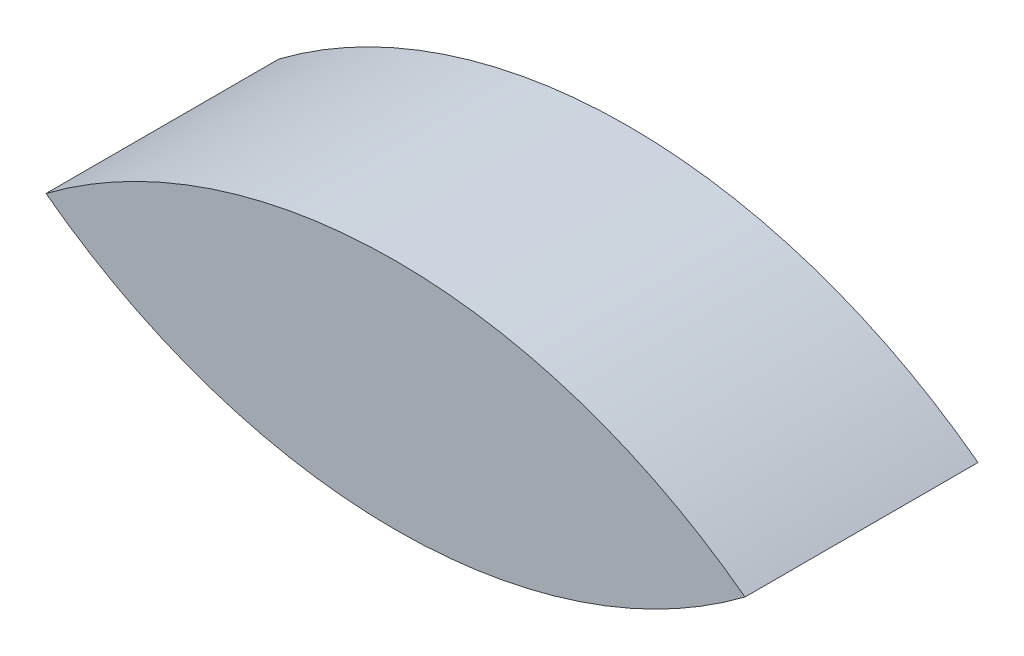
SolidWorks part; units mm, degrees
ref_plane "Спереди"
ref_plane "Сверху" through (0, 0, 0) normal (0, 1, 0) x (1, 0, 0)
ref_plane "Справа" through (0, 0, 0) normal (1, 0, 0) x (0, 0, -1)
sketch "Эскиз1" plane through (0, 0, 0) normal (0, 0, 1) x (1, 0, 0)
  line L0 (-15, 0) -> (15, 0) construction
  line L1 (15, -5) -> (-15, -5) construction
  line L2 (15, -5) -> (15, 5) construction
  line L3 (15, 5) -> (-15, 5) construction
  line L4 (-15, -5) -> (-15, 5) construction
  line L5 (15, -5) -> (-15, 5) construction
  line L6 (15, 5) -> (-15, -5) construction
  arc A0 (-15, 0) -> (15, 0) centre (0, -20) cw
  arc A1 (-15, 0) -> (15, 0) centre (0, 20) ccw
  point P0 (0, 0)
  dimension "D1" = 10
  dimension "D2" = 30
extrude "Бобышка-Вытянуть1" add sketch "Эскиз1" along normal mid plane 10
